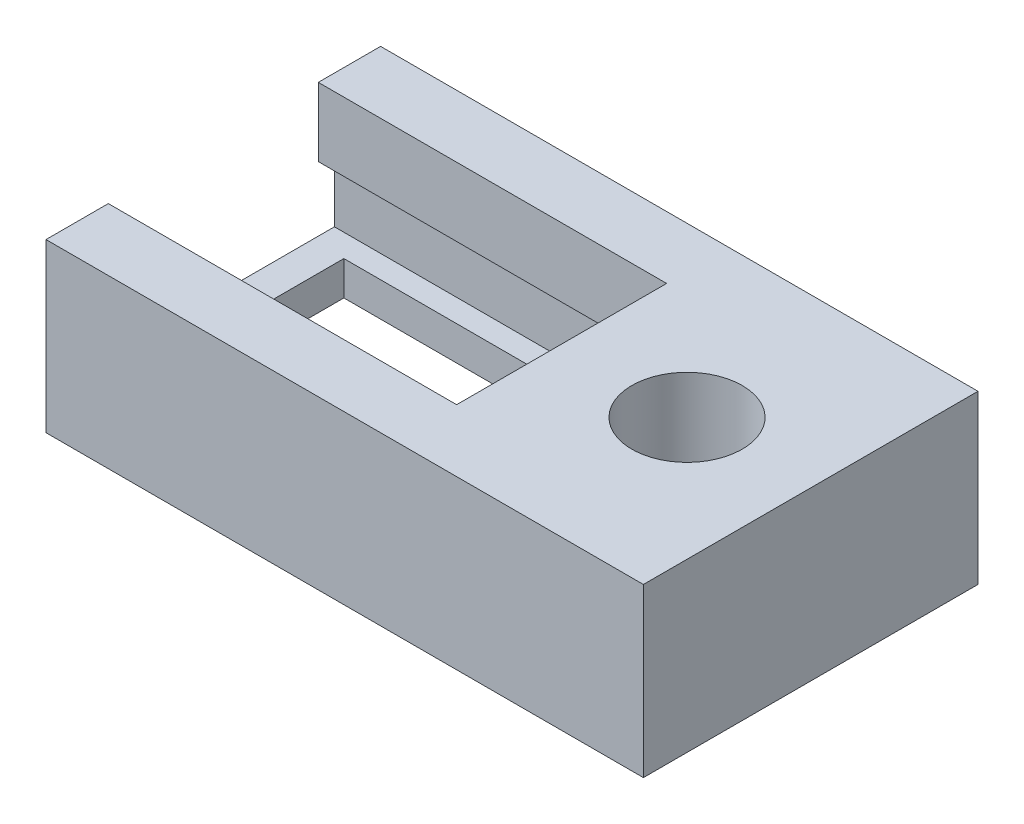
SolidWorks part; units mm, degrees
ref_plane "Front Plane" through (0, 0, 0) normal (0, 0, 1) x (1, 0, 0)
ref_plane "Top Plane" through (0, 0, 0) normal (0, 1, 0) x (1, 0, 0)
ref_plane "Right Plane" through (0, 0, 0) normal (1, 0, 0) x (0, 0, -1)
sketch "Sketch2" plane through (0, 0, 0) normal (0, 1, 0) x (1, 0, 0)
  line L0 (-2.8537, -5) -> (-2.8537, 5)
  line L5 (3.3811, -5.924) -> (-2.8537, 5) construction
  line L6 (2.8537, 5) -> (-2.8537, -5) construction
  line L7 (-2.8537, 5) -> (15, 5)
  line L8 (15, 5) -> (15, -5)
  line L9 (15, -5) -> (-2.8537, -5)
  point P0 (0, 0)
extrude "Boss-Extrude2" add sketch "Sketch2" along normal blind 5
sketch "Sketch4" plane through (-2.8537, 0, 0) normal (-1, 0, 0) x (0, 0, 1)
  line L7 (3.48, 1.02) -> (-3.62, 1.02)
  line L8 (3.48, 1.02) -> (3.48, 2.9481)
  line L9 (3.48, 2.9481) -> (-3.62, 2.9481)
  line L10 (-3.62, 1.02) -> (-3.62, 2.9481)
  line L11 (3.48, 1.02) -> (-3.62, 2.9481) construction
  line L12 (3.48, 2.9481) -> (-3.62, 1.02) construction
  point P12 (-0.07, 1.984)
extrude "Cut-Extrude1" cut sketch "Sketch4" against normal blind 9.3
sketch "Sketch6" plane through (0, 0, 0) normal (0, 1, 0) x (1, 0, 0)
  line L2 (7.5564, -3.1377) -> (-7.5564, -3.1377)
  line L3 (7.5564, -3.1377) -> (7.5564, 3.1377)
  line L4 (7.5564, 3.1377) -> (-7.5564, 3.1377)
  line L5 (-7.5564, -3.1377) -> (-7.5564, 3.1377)
  line L6 (7.5564, -3.1377) -> (-7.5564, 3.1377) construction
  line L7 (7.5564, 3.1377) -> (-7.5564, -3.1377) construction
  point P2 (0, 0)
extrude "Cut-Extrude4" cut sketch "Sketch6" along normal blind 9.3 from surface at 1.02 starting at face at (1.7963, 1.02, -0.07)
sketch "Sketch7" plane through (0, 0, 0) normal (0, -1, 0) x (1, 0, 0)
  circle A1 centre (11.3269, 0.0231) radius 1.65
extrude "Cut-Extrude7" cut sketch "Sketch7" against normal through all
sketch "Sketch9" plane through (0, 1.02, 0) normal (0, 1, 0) x (1, 0, 0)
  line L0 (-1.8905, 2.9392) -> (7.2776, 2.9392)
  line L1 (7.2776, 2.9392) -> (7.2776, -2.8853)
  line L2 (7.2776, -2.8853) -> (-1.8905, -2.8853)
  line L3 (-1.8905, -2.8853) -> (-1.8905, 2.9392)
extrude "Cut-Extrude8" cut sketch "Sketch9" against normal through all
